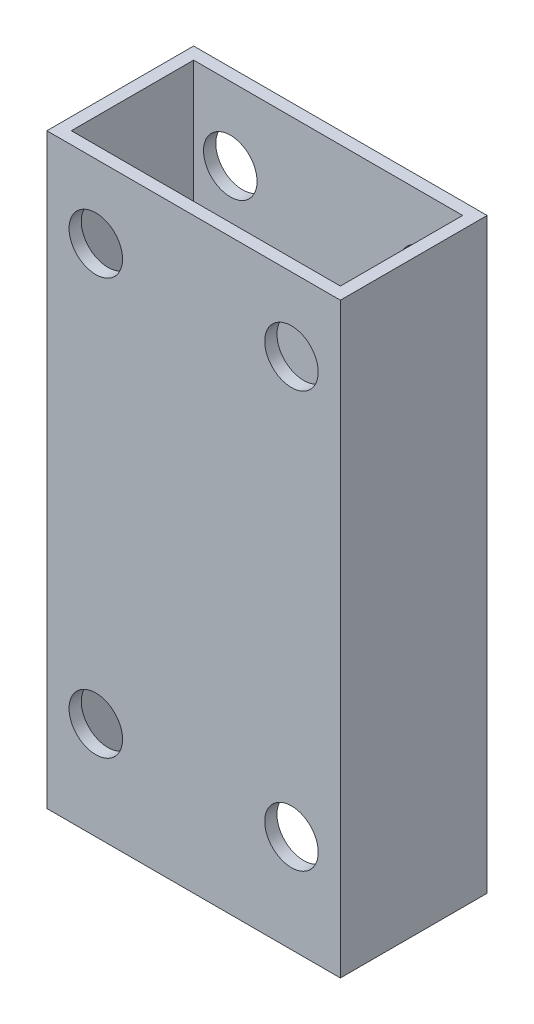
SolidWorks part; units mm, degrees
material "6061-T6 (SS)"
ref_plane "Front" through (0, 0, 0) normal (0, 0, 1) x (1, 0, 0)
ref_plane "Top" through (0, 0, 0) normal (0, 1, 0) x (1, 0, 0)
ref_plane "Right" through (0, 0, 0) normal (1, 0, 0) x (0, 0, -1)
sketch "Sketch1" plane through (0, 0, 0) normal (0, 1, 0) x (1, 0, 0)
  line L1 (-38.1, -19.05) -> (38.1, -19.05)
  line L2 (-38.1, -19.05) -> (-38.1, 19.05)
  line L3 (-38.1, 19.05) -> (38.1, 19.05)
  line L4 (38.1, -19.05) -> (38.1, 19.05)
  line L5 (-38.1, -19.05) -> (38.1, 19.05) construction
  line L6 (-38.1, 19.05) -> (38.1, -19.05) construction
  point P0 (0, 0)
  dimension "D1" = 76.2
  dimension "D2" = 38.1
extrude "Extrude1" add sketch "Sketch1" along normal mid plane 152.4
sketch "Sketch2" plane through (0, 76.2, 0) normal (0, 1, 0) x (1, 0, 0)
  line L8 (34.925, -15.875) -> (34.925, 15.875)
  line L9 (34.925, 15.875) -> (-34.925, 15.875)
  line L10 (-34.925, 15.875) -> (-34.925, -15.875)
  line L11 (-34.925, -15.875) -> (34.925, -15.875)
  line L12 (34.925, -15.875) -> (34.925, 15.875)
  line L13 (34.925, 15.875) -> (-34.925, 15.875)
  line L14 (-34.925, 15.875) -> (-34.925, -15.875)
  line L15 (-34.925, -15.875) -> (34.925, -15.875)
  dimension "D1" = 3.175
extrude "Extrude2" cut sketch "Sketch2" against normal through all
hole_wizard "1/2 Clearance Hole1" positions "Sketch4" profile "Sketch3" hole size "1/2" standard "Ansi Inch" end condition through all
sketch "Sketch4" plane through (0, 0, 19.05) normal (0, 0, 1) x (1, 0, 0)
  line L0 (-38.1, 57.15) -> (38.1, 57.15) construction
  line L1 (-38.1, 76.2) -> (-38.1, -76.2) construction
  line L2 (38.1, 76.2) -> (38.1, -76.2) construction
  line L4 (0, 76.2) -> (0, -76.2) construction
  line L5 (-38.1, 76.2) -> (38.1, 76.2) construction
  line L6 (-25.4, 76.2) -> (-25.4, -76.2) construction
  line L7 (-38.1, -76.2) -> (38.1, -76.2) construction
  line L9 (25.4, 76.2) -> (25.4, -76.2) construction
  line L13 (-38.1, -50.8) -> (38.1, -50.8) construction
  point P0 (25.4, 57.15)
  point P1 (-25.4, 57.15)
  point P41 (-25.4, -50.8)
  point P43 (25.4, -50.8)
  dimension "D1" = 25.4
  dimension "D2" = 25.4
  dimension "D3" = 19.05
  dimension "D4" = 25.4
sketch "Sketch3" plane through (25.4, 57.15, 19.05) normal (1, 0, 0) x (0, -1, 0)
  line L0 (0, 0) -> (0, 38.1)
  line L1 (0, 38.1) -> (6.9456, 38.1)
  line L2 (6.9456, 38.1) -> (6.9456, 0)
  line L5 (6.9456, 0) -> (0, 0)
  line L11 (0, -6.35) -> (0, 107.95) construction
  dimension "Thru Hole Dia." = 13.8913
  dimension "Thru Hole Depth" = 38.1
